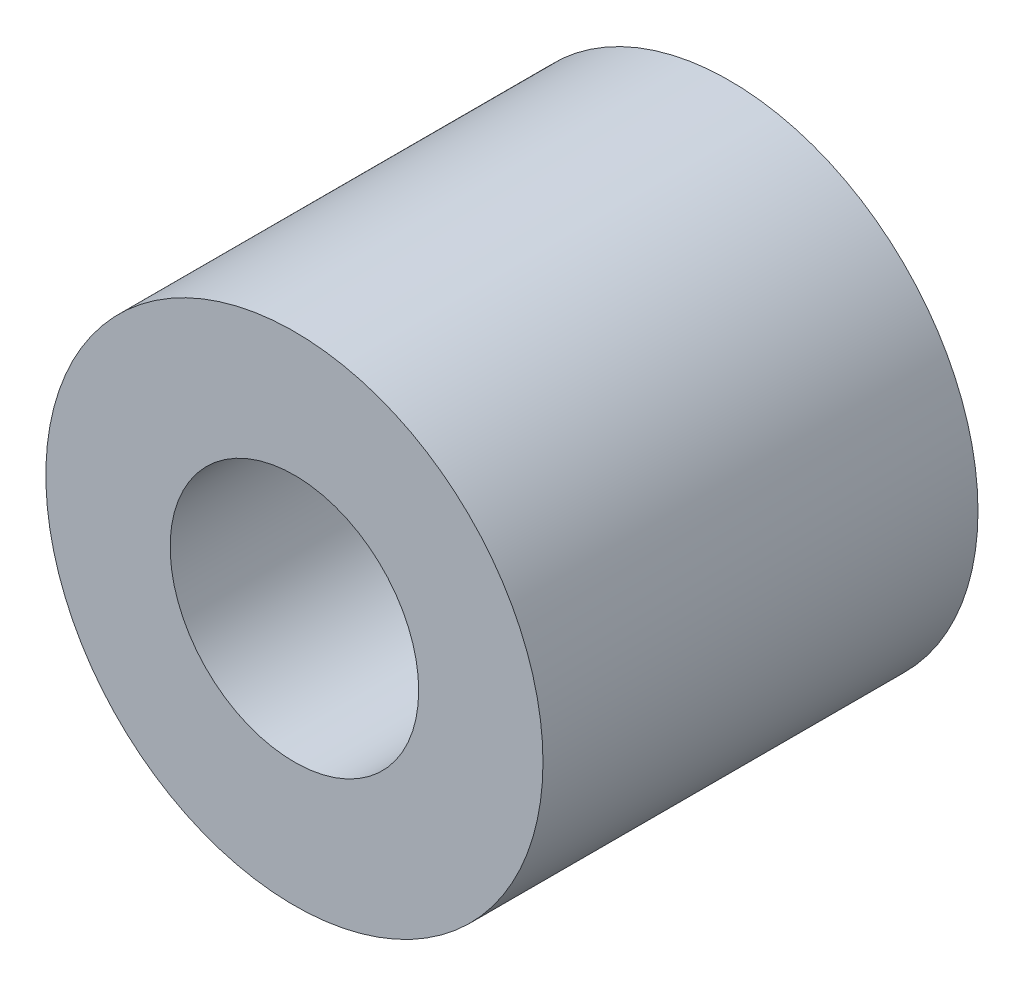
SolidWorks part; units mm, degrees
ref_plane "Front Plane" through (0, 0, 0) normal (0, 0, 1) x (1, 0, 0)
ref_plane "Top Plane" through (0, 0, 0) normal (0, 1, 0) x (1, 0, 0)
ref_plane "Right Plane" through (0, 0, 0) normal (1, 0, 0) x (0, 0, -1)
sketch "Sketch1" plane through (0, 0, 0) normal (0, 0, 1) x (1, 0, 0)
  circle A0 centre (0, 0) radius 8
  dimension "D1" = 16
extrude "Boss-Extrude1" add sketch "Sketch1" along normal blind 2
sketch "Sketch2" plane through (0, 0, 2) normal (0, 0, 1) x (1, 0, 0)
  circle A1 centre (0, 0) radius 4
  circle A2 centre (0, 0) radius 8 construction
  circle A3 centre (0, 0) radius 8
  dimension "D1" = 8
extrude "Boss-Extrude2" add sketch "Sketch2" along normal blind 12
